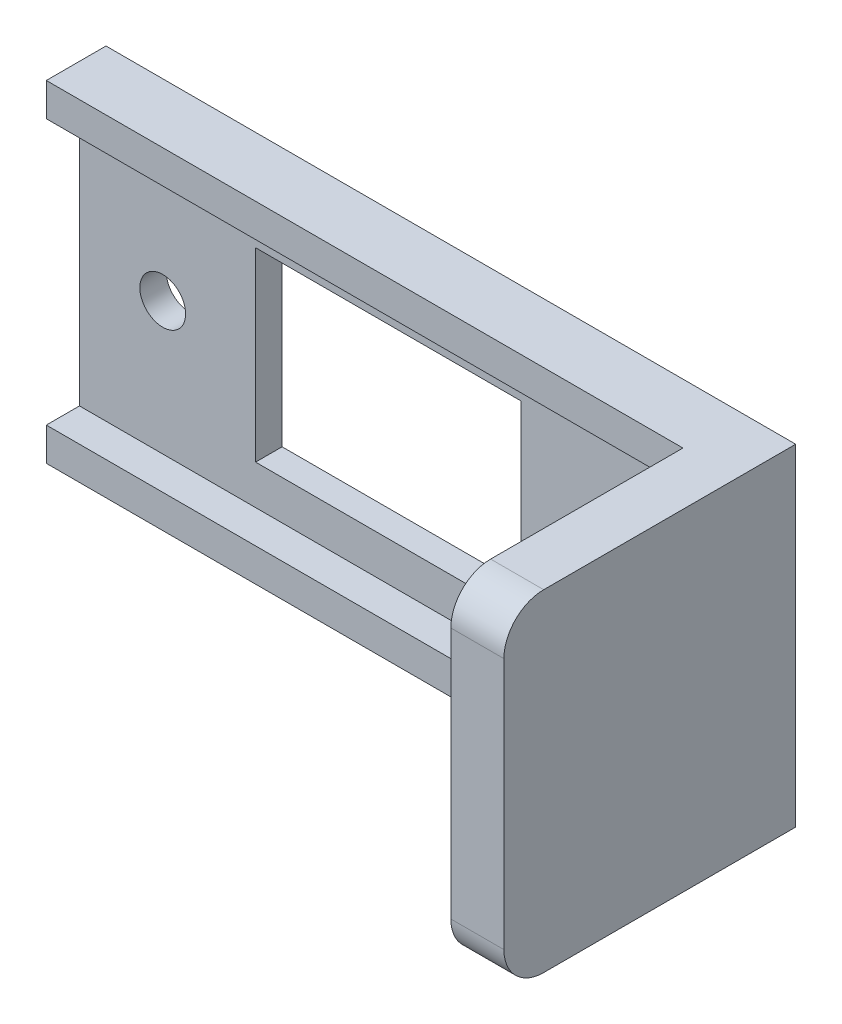
SolidWorks part; units mm, degrees
ref_plane "Front Plane" through (0, 0, 0) normal (0, 0, 1) x (1, 0, 0)
ref_plane "Top Plane" through (0, 0, 0) normal (0, 1, 0) x (1, 0, 0)
ref_plane "Right Plane" through (0, 0, 0) normal (1, 0, 0) x (0, 0, -1)
sketch "Sketch1" plane through (0, 0, 0) normal (0, 0, 1) x (1, 0, 0)
  line L1 (0, 0) -> (52, 0)
  line L2 (0, 0) -> (0, -25)
  line L3 (0, -25) -> (52, -25)
  line L4 (52, 0) -> (52, -25)
  dimension "D1" = 52
  dimension "D2" = 25
extrude "Boss-Extrude1" add sketch "Sketch1" along normal blind 2
ref_plane "Plane1" through (0, 0, 2) normal (0, 0, -1) x (-1, 0, 0)
sketch "Sketch2" plane through (0, 0, 2) normal (0, 0, -1) x (-1, 0, 0)
  line L1 (-48, 0) -> (-52, 0)
  line L2 (-48, 0) -> (-48, -25)
  line L3 (-48, -25) -> (-52, -25)
  line L4 (-52, 0) -> (-52, -25)
  dimension "D1" = 4
extrude "Boss-Extrude2" add sketch "Sketch2" against normal blind 20
fillet "Fillet1" radius 3 2 edges at (50, -25, 22) (50, 0, 22)
sketch "Sketch4" plane through (0, 0, 2) normal (0, 0, 1) x (1, 0, 0)
  line L0 (48, 0) -> (0, 0) construction
  circle A0 centre (41.2777, -12.5) radius 1.725
  circle A1 centre (6.2777, -12.5) radius 1.725
  dimension "D1" = 35
  dimension "D2" = 12.5
  dimension "D3" = 12.5
extrude "Cut-Extrude2" cut sketch "Sketch4" against normal up to surface (2 mm away) up to face at (26, -12.5, 0)
sketch "Sketch5" plane through (0, 0, 2) normal (0, 0, -1) x (-1, 0, 0)
  line L6 (0, 0) -> (0, -25) construction
  line L7 (-48, -25) -> (0, -25)
  line L8 (-48, -25) -> (-48, -22.5)
  line L9 (-48, -22.5) -> (0, -22.5)
  line L10 (0, -25) -> (0, -22.5)
  line L11 (-4.5527, -12.5) -> (7.0358, -12.5) construction
  line L12 (-48, -2.5) -> (0, -2.5)
  line L13 (0, 0) -> (0, -2.5)
  line L14 (-48, 0) -> (0, 0)
  line L15 (-48, 0) -> (-48, -2.5)
  circle A0 centre (-6.2777, -12.5) radius 1.725 construction
  dimension "D1" = 2.5
extrude "Boss-Extrude3" add sketch "Sketch5" against normal blind 2.5
sketch "Sketch6" plane through (0, 0, 2) normal (0, 0, 1) x (1, 0, 0)
  line L1 (33.2777, -5.531) -> (13.2777, -5.531)
  line L2 (33.2777, -5.531) -> (33.2777, -19.531)
  line L3 (33.2777, -19.531) -> (13.2777, -19.531)
  line L4 (13.2777, -5.531) -> (13.2777, -19.531)
  circle A0 centre (6.2777, -12.5) radius 1.725 construction
  dimension "D3" = 7
  dimension "D1" = 14
  dimension "D2" = 20
extrude "Cut-Extrude3" cut sketch "Sketch6" against normal up to surface (2 mm away) up to face at (43.0027, -12.5, 0)
